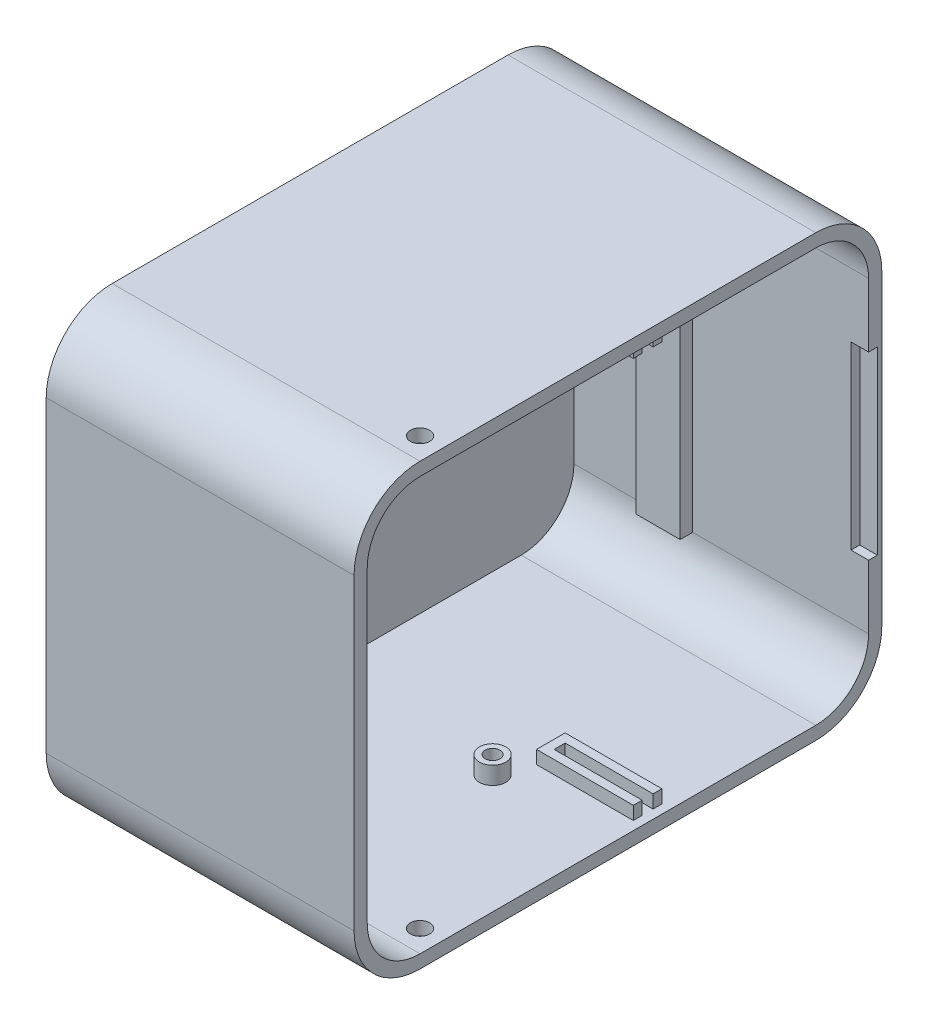
SolidWorks part; units mm, degrees
ref_plane "Front Plane" through (0, 0, 0) normal (0, 0, 1) x (1, 0, 0)
ref_plane "Top Plane" through (0, 0, 0) normal (0, 1, 0) x (1, 0, 0)
ref_plane "Right Plane" through (0, 0, 0) normal (1, 0, 0) x (0, 0, -1)
sketch "Sketch1" plane through (0, 0, 0) normal (1, 0, 0) x (0, 0, -1)
  line L1 (-60, 50) -> (60, 50)
  line L2 (-60, 50) -> (-60, -50)
  line L3 (-60, -50) -> (60, -50)
  line L4 (60, 50) -> (60, -50)
  line L5 (-60, 50) -> (60, -50) construction
  line L6 (-60, -50) -> (60, 50) construction
  point P0 (0, 0)
  dimension "D1" = 100
  dimension "D2" = 120
extrude "Boss-Extrude2" add sketch "Sketch1" along normal blind 70
fillet "Fillet1" radius 15 4 edges at (35, 50, -60) (35, -50, -60) (35, -50, 60) (35, 50, 60)
shell "Shell2" thickness 3
sketch "Sketch3" plane through (0, 0, -57) normal (0, 0, 1) x (1, 0, 0)
  line L0 (70, -35) -> (70, 35) construction
  line L1 (66, 20.5) -> (70, 20.5)
  line L2 (66, 20.5) -> (66, -20.5)
  line L3 (66, -20.5) -> (70, -20.5)
  line L4 (70, 20.5) -> (70, -20.5)
  line L5 (70, -35) -> (3, -35) construction
  dimension "D1" = 0
  dimension "D2" = 4
  dimension "D3" = 41
  dimension "D4" = 14.5
extrude "Cut-Extrude1" cut sketch "Sketch3" against normal blind 2
sketch "Sketch4" plane through (0, 0, -57) normal (0, 0, 1) x (1, 0, 0)
  line L0 (70, 20.5) -> (70, 35) construction
  line L7 (3, 35) -> (70, 35) construction
  line L8 (30, 35) -> (20, 35)
  line L9 (30, 35) -> (30, -35)
  line L10 (30, -35) -> (20, -35)
  line L11 (20, 35) -> (20, -35)
  line L12 (70, -35) -> (3, -35) construction
  dimension "D1" = 10
  dimension "D2" = 40
extrude "Boss-Extrude3" add sketch "Sketch4" along normal blind 2.85
sketch "Sketch6" plane through (0, -50, 0) normal (0, -1, 0) x (1, 0, 0)
  line L5 (70, 45) -> (0, 45) construction
  line L6 (70, 45) -> (70, -45) construction
  circle A1 centre (65, 40) radius 2.2
  point P0 (65, 40)
  dimension "D3" = 4.4
  dimension "D1" = 5
  dimension "D2" = 5
sketch "Sketch15" plane through (0, 47, 0) normal (0, -1, 0) x (1, 0, 0)
  line L0 (46, -5.5) -> (68, -5.5)
  line L1 (48, -10) -> (68, -10)
  line L3 (46, -12) -> (68, -12)
  line L4 (68, -10) -> (68, -12)
  line L5 (48, -10) -> (68, -12) construction
  line L6 (46, -9.7617) -> (68, -10) construction
  line L7 (70, -45) -> (70, 45) construction
  line L9 (30, -57) -> (70, -57) construction
  line L10 (48, -7.5) -> (68, -7.5)
  line L11 (68, -5.5) -> (68, -7.5)
  line L12 (46, -7.6367) -> (68, -7.5) construction
  line L13 (48, -7.5) -> (68, -5.5) construction
  line L14 (70, 45) -> (70, -45) construction
  line L17 (48, -7.5) -> (48, -10)
  line L19 (46, -5.5) -> (46, -12)
  point P0 (45.5707, -9.7571)
  point P9 (46.6746, -7.6325)
  dimension "D1" = 2
  dimension "D2" = 45
  dimension "D3" = 2
  dimension "D4" = 20
  dimension "D5" = 2
  dimension "D6" = 2.5
  dimension "D7" = 2
  dimension "D8" = 2
sketch "Sketch16" plane through (3, 0, 0) normal (1, 0, 0) x (0, 0, -1)
  line L0 (-45, -47) -> (45, -47) construction
  line L1 (-47, -32) -> (4, -32) construction
  line L2 (-47, -32) -> (-47, 42) construction
  line L3 (-47, 42) -> (4, 42) construction
  line L4 (4, -32) -> (4, 42) construction
  line L5 (-57, 35) -> (-57, -35) construction
  circle A0 centre (1.5, -29.8) radius 3.5
  circle A1 centre (-0.4, 36.2) radius 3.5
  circle A2 centre (1.5, -29.8) radius 2.2
  circle A3 centre (-0.4, 36.2) radius 2.2
  circle A5 centre (-38, 35) radius 1.5
  circle A6 centre (-41.6756, -27.3743) radius 1.5
  dimension "D7" = 7
  dimension "D10" = 7
  dimension "D11" = 14
  dimension "D13" = 4.4
  dimension "D14" = 4.4
  dimension "D15" = 3
  dimension "D16" = 3
  dimension "D1" = 74
  dimension "D2" = 51
  dimension "D3" = 15
  dimension "D4" = 10
  dimension "D5" = 2.5
  dimension "D6" = 2.2
  dimension "D8" = 5.8
  dimension "D9" = 4.4
  dimension "D12" = 42
extrude "Boss-Extrude5" add sketch "Sketch16" along normal blind 5
extrude "Boss-Extrude6" add sketch "Sketch15" along normal blind 3
sketch "Sketch18" plane through (0, -47, 0) normal (0, 1, 0) x (1, 0, 0)
sketch "Sketch19" plane through (0, 0, 0) normal (-1, 0, 0) x (0, 0, 1)
  line L1 (-15, 15) -> (15, 15)
  line L2 (-15, 15) -> (-15, -15)
  line L3 (-15, -15) -> (15, -15)
  line L4 (15, 15) -> (15, -15)
  line L5 (-15, 15) -> (15, -15) construction
  line L6 (-15, -15) -> (15, 15) construction
  point P0 (0, 0)
  dimension "D1" = 30
  dimension "D2" = 30
mirror "Mirror1" about plane through (0, 0, 0) normal (0, 1, 0) of "Boss-Extrude6"
sketch "Sketch21" plane through (0, -47, 0) normal (0, 1, 0) x (1, 0, 0)
  line L0 (68, 5.5) -> (46, 5.5) construction
  line L1 (25, 5.5) -> (46, 5.5)
  line L2 (25, 5.5) -> (25, -42.5)
  line L3 (25, -42.5) -> (46, -42.5)
  line L4 (46, 5.5) -> (46, -42.5)
  line L5 (25, 5.5) -> (46, -42.5) construction
  line L6 (25, -42.5) -> (46, 5.5) construction
  line L8 (46, 5.5) -> (46, 12) construction
  point P0 (35.5, -18.5)
  dimension "D1" = 48
  dimension "D2" = 21
  dimension "D3" = 0
  dimension "D4" = 0
sketch "Sketch23" plane through (0, -47, 0) normal (0, 1, 0) x (1, 0, 0)
  line L0 (25, -42.5) -> (46, -42.5) construction
  line L1 (46, 5.5) -> (46, -42.5) construction
  line L2 (25, 5.5) -> (25, -42.5) construction
  line L3 (25, 5.5) -> (46, 5.5) construction
  circle A0 centre (43, -1.5) radius 1.7
  circle A1 centre (28, -32.5) radius 1.7
  circle A2 centre (43, -1.5) radius 3
  circle A3 centre (28, -32.5) radius 3
  dimension "D1" = 3.4
  dimension "D2" = 3.4
  dimension "D3" = 10
  dimension "D4" = 18
  dimension "D5" = 18
  dimension "D6" = 7
extrude "Boss-Extrude10" add sketch "Sketch23" along normal blind 4
extrude "Cut-Extrude2" cut sketch "Sketch6" against normal through all
sketch "Sketch24" plane through (3, 0, 0) normal (1, 0, 0) x (0, 0, -1)
  line L1 (-10, 10) -> (10, 10)
  line L2 (-10, 10) -> (-10, -10)
  line L3 (-10, -10) -> (10, -10)
  line L4 (10, 10) -> (10, -10)
  line L5 (-10, 10) -> (10, -10) construction
  line L6 (-10, -10) -> (10, 10) construction
  circle A0 centre (-10, 10) radius 4
  circle A1 centre (10, 10) radius 4
  circle A2 centre (-10, -10) radius 4
  circle A3 centre (10, -10) radius 4
  point P0 (0, 0)
  dimension "D3" = 8
  dimension "D4" = 8
  dimension "D5" = 8
  dimension "D6" = 8
  dimension "D1" = 20
  dimension "D2" = 20
extrude "Cut-Extrude3" cut sketch "Sketch24" against normal up to surface (3 mm away) contours A0 | A1 | A2 | A3 up to face at (0, 0, 0)
